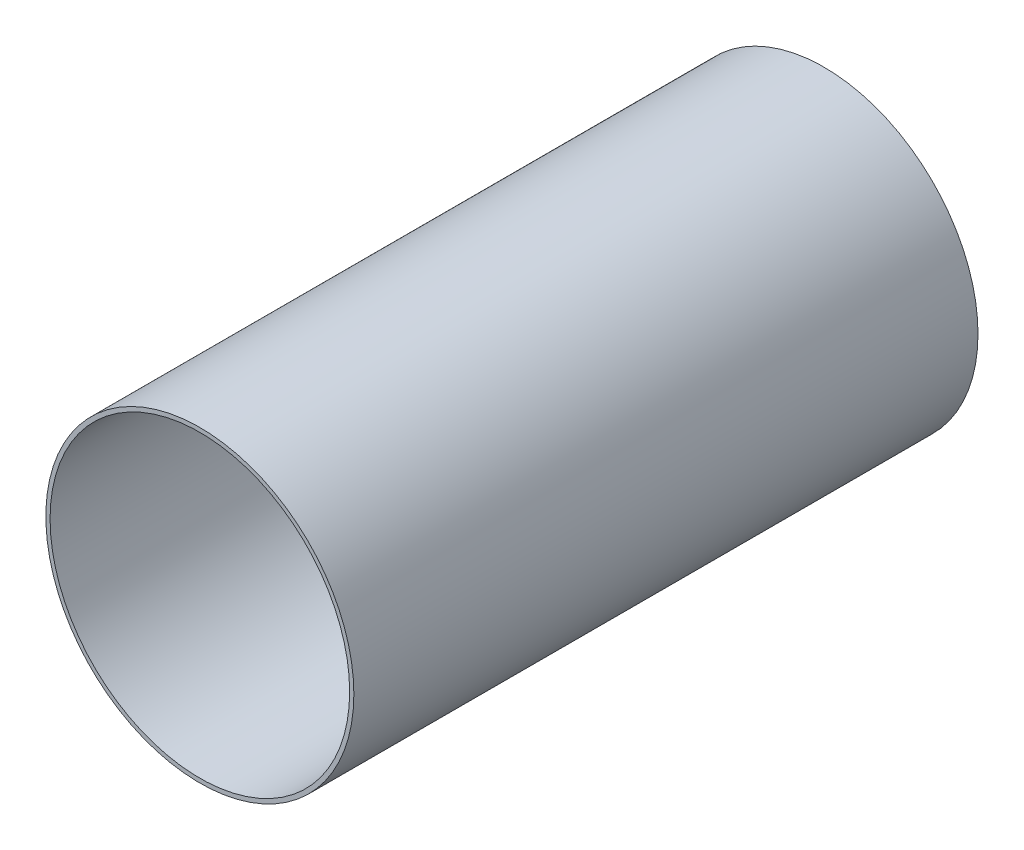
SolidWorks part; units mm, degrees
material "A-Glass Fiber"
ref_plane "Front Plane" through (0, 0, 0) normal (1, 0, 0) x (0, 1, 0)
ref_plane "Top Plane" through (0, 0, 0) normal (0, 0, 1) x (0, 1, 0)
ref_plane "Right Plane" through (0, 0, 0) normal (0, 1, 0) x (-1, 0, 0)
sketch "Sketch1" plane through (0, 0, 0) normal (0, 0, 1) x (0, 1, 0)
  circle A0 centre (0, 0) radius 48
  circle A1 centre (0, 0) radius 49.35
  dimension "D1" = 96
  dimension "D2" = 98.7
extrude "Boss-Extrude1" add sketch "Sketch1" along normal blind 200
ref_point "Point2"
